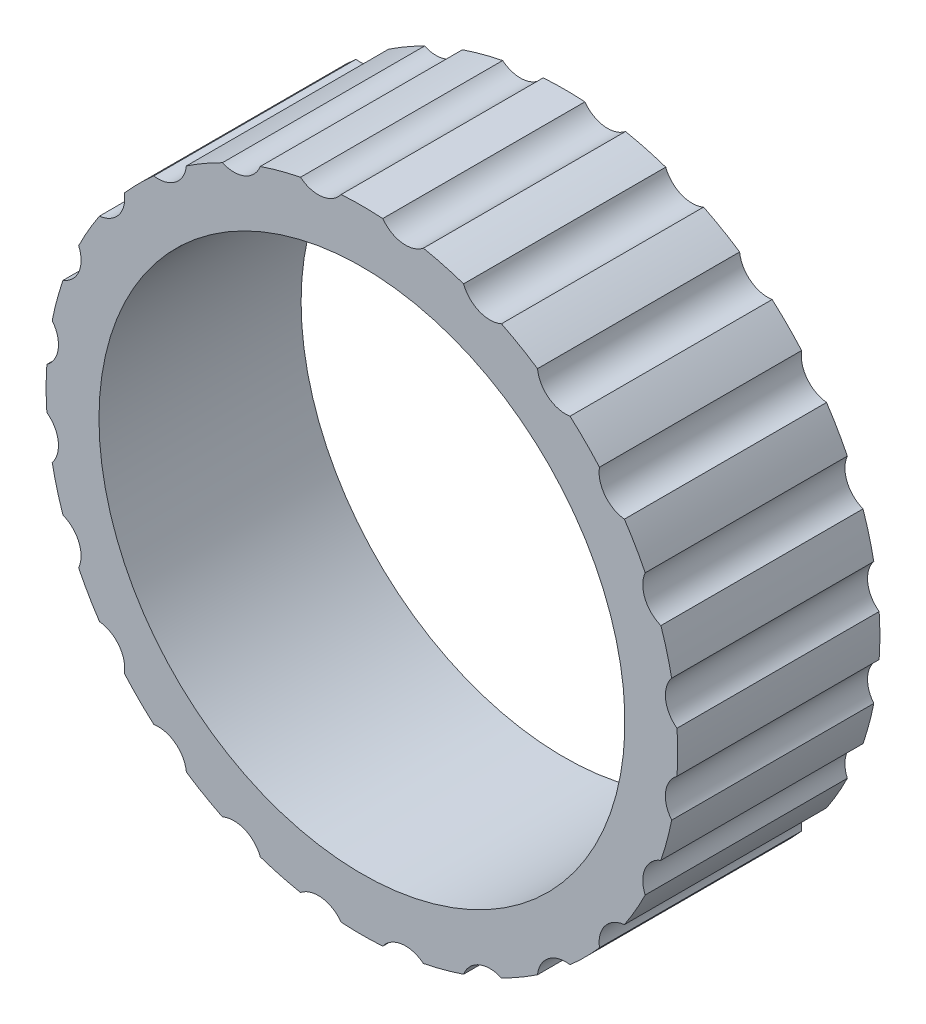
SolidWorks part; units mm, degrees
ref_plane "Front Plane" through (0, 0, 0) normal (0, 0, 1) x (1, 0, 0)
ref_plane "Top Plane" through (0, 0, 0) normal (0, 1, 0) x (1, 0, 0)
ref_plane "Right Plane" through (0, 0, 0) normal (1, 0, 0) x (0, 0, -1)
sketch "PD" plane through (0, 0, 0) normal (0, 0, 1) x (1, 0, 0)
  circle A0 centre (0, 0) radius 19.0986
  dimension "PD" = 38.1972
extrude "half width" add sketch "PD" along normal blind 10.67
sketch "Sketch3" plane through (0, 0, 10.67) normal (0, 0, 1) x (1, 0, 0)
  line L0 (0, 0) -> (0, 18.2286) construction
  line L1 (0, 18.2286) -> (0.4071, 18.2286)
  line L2 (0, 0) -> (2.3049, 17.5075) construction
  line L3 (0, 18.2286) -> (0, 19.0986)
  line L4 (4.7179, 17.6075) -> (4.9431, 18.4478)
  line L5 (4.7179, 17.6075) -> (4.3247, 17.7128)
  line L6 (2.3049, 17.5075) -> (2.4929, 18.9352) construction
  arc A0 (0.4071, 18.2286) -> (0.8321, 17.7334) centre (0.4071, 17.7986) cw
  arc A1 (0.8321, 17.7334) -> (3.786, 17.3445) centre (2.3049, 17.5075) ccw
  circle A2 centre (0, 0) radius 19.0986 construction
  arc A3 (0, 19.0986) -> (4.9431, 18.4478) centre (0, 0) cw
  arc A4 (4.3247, 17.7128) -> (3.786, 17.3445) centre (4.2134, 17.2975) ccw
  point P8 (2.1104, 16.0303)
  dimension "D1" = 0.43
  dimension "D2" = 1.49
  dimension "D5" = 2.93
  dimension "D3" = 0.87
  dimension "D4" = 7.5
extrude "Teeth " cut sketch "Sketch3" against normal up to surface (10.67 mm away) up to face at (19.0986, 0, 0)
pattern_circular "CirPattern1" count 24 over 360 about axis through (0, 0, 0) along (0, 0, 1) of "Teeth "
sketch "Sketch4" plane through (0, 0, 0) normal (0, 0, -1) x (-1, 0, 0)
  line L0 (0, 0) -> (2.1757, 16.526) construction
  circle A0 centre (0, 0) radius 16.6686
  circle A1 centre (0, 0) radius 20.0229
  arc A2 (0.8321, 17.7334) -> (3.786, 17.3445) centre (2.3049, 17.5075) ccw construction
  point P4 (2.1104, 16.0303)
  point P5 (2.1757, 16.526)
  dimension "D1" = 0.5
extrude "Cut-Extrude1" cut sketch "Sketch4" against normal through all
sketch "Sketch5" plane through (0, 0, 0) normal (0, 0, -1) x (-1, 0, 0)
  circle A0 centre (0, 0) radius 13.881
extrude "Cut-Extrude2" cut sketch "Sketch5" against normal through all
equation "\"n\"= 24"
equation "\"p\"= 5'pitch"
equation "\"pd\"= \"n\" * \"p\" / pi'pitch diameter"
equation "\"PD@PD\"=\"pd\""
equation "\"D1@CirPattern1\"=\"n\""
equation "\"Bolt diameter\"= 3mm"
equation "\"D1@Sketch6\"= \"Bolt diameter\""
